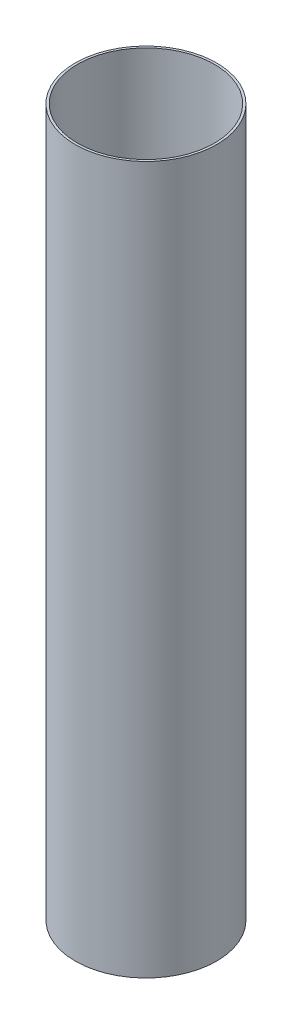
SolidWorks part; units mm, degrees
material "PBT General Purpose"
ref_plane "Front Plane" through (0, 0, 0) normal (0, 0, 1) x (1, 0, 0)
ref_plane "Top Plane" through (0, 0, 0) normal (0, 1, 0) x (1, 0, 0)
ref_plane "Right Plane" through (0, 0, 0) normal (1, 0, 0) x (0, 0, -1)
sketch "Sketch1" plane through (0, 0, 0) normal (0, 1, 0) x (1, 0, 0)
  circle A0 centre (0, 0) radius 31
extrude "Boss-Extrude1" add sketch "Sketch1" along normal blind 310
sketch "Sketch2" plane through (0, 310, 0) normal (0, 1, 0) x (1, 0, 0)
  circle A0 centre (0, 0) radius 30
extrude "Cut-Extrude1" cut sketch "Sketch2" against normal blind 300
